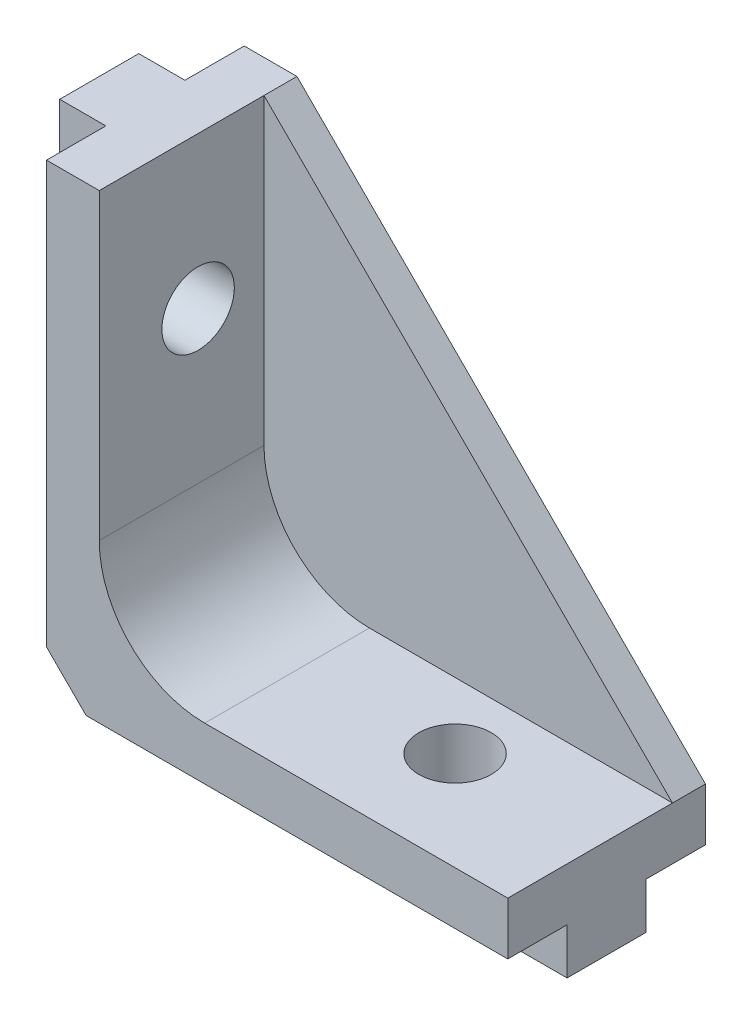
SolidWorks part; units mm, degrees
ref_plane "Front" through (0, 0, 0) normal (0, 0, 1) x (1, 0, 0)
ref_plane "Top" through (0, 0, 0) normal (0, 1, 0) x (1, 0, 0)
ref_plane "Right" through (0, 0, 0) normal (1, 0, 0) x (0, 0, -1)
sketch "Sketch1" plane through (0, 0, 0) normal (0, 0, 1) x (1, 0, 0)
  line L0 (0, 0) -> (0, 35)
  line L1 (0, 35) -> (4, 35)
  line L2 (4, 35) -> (35, 4)
  line L3 (35, 4) -> (35, 0)
  line L4 (35, 0) -> (0, 0)
  dimension "D1" = 4
  dimension "D2" = 35
extrude "Boss-Extrude1" add sketch "Sketch1" along normal blind 2.5
sketch "Sketch2" plane through (0, 0, 2.5) normal (0, 0, 1) x (1, 0, 0)
  line L0 (35, 0) -> (35, 4) construction
  line L1 (0, 0) -> (35, 0) construction
  line L2 (4, 35) -> (0, 35) construction
  line L3 (0, 35) -> (0, 0) construction
  line L4 (35, 0) -> (35, 4)
  line L5 (0, 0) -> (35, 0)
  line L6 (4, 35) -> (0, 35)
  line L7 (0, 35) -> (0, 0)
  line L8 (4, 35) -> (4, 4)
  line L9 (4, 4) -> (35, 4)
extrude "Boss-Extrude2" add sketch "Sketch2" along normal blind 12.5
sketch "Sketch5" plane through (0, 0, 0) normal (0, -1, 0) x (1, 0, 0)
  line L0 (35, 15) -> (35, 0) construction
  line L1 (35, 10.5) -> (4.5, 10.5)
  line L2 (35, 10.5) -> (35, 4.5)
  line L3 (35, 4.5) -> (4.5, 4.5)
  line L4 (4.5, 10.5) -> (4.5, 4.5)
  point P7 (35, 7.5)
  point P8 (35, 7.5)
  dimension "D1" = 30.5
  dimension "D2" = 6
extrude "Boss-Extrude3" add sketch "Sketch5" along normal blind 3.5
sketch "Sketch6" plane through (0, 0, 0) normal (-1, 0, 0) x (0, 0, 1)
  line L0 (15, 35) -> (0, 35) construction
  line L1 (10.5, 35) -> (4.5, 35)
  line L2 (10.5, 35) -> (10.5, 4.5)
  line L3 (10.5, 4.5) -> (4.5, 4.5)
  line L4 (4.5, 35) -> (4.5, 4.5)
  point P6 (7.5, 35)
  point P7 (7.5, 35)
  dimension "D1" = 6
  dimension "D2" = 30.5
extrude "Boss-Extrude4" add sketch "Sketch6" along normal blind 3.5
sketch "Sketch3" plane through (4, 0, 0) normal (1, 0, 0) x (0, 0, -1)
  line L0 (-7.5, 35) -> (-7.5, 23.5) construction
  line L1 (-10.5, 35) -> (-4.5, 35) construction
  line L2 (-7.5, 23.5) -> (-7.5, 0) construction
  line L5 (-15, 0) -> (0, 0) construction
  circle A0 centre (-7.5, 23.5) radius 2.75
  point P7 (-7.5, 35)
  point P10 (-7.5, 0)
  dimension "D1" = 5.5
  dimension "D2" = 23.5
extrude "Cut-Extrude1" cut sketch "Sketch3" against normal up to next
sketch "Sketch4" plane through (0, 4, 0) normal (0, 1, 0) x (1, 0, 0)
  line L0 (0, -7.5) -> (23.5, -7.5) construction
  line L2 (23.5, -7.5) -> (35, -7.5) construction
  line L4 (0, -15) -> (0, 0) construction
  line L6 (35, -4.5) -> (35, -10.5) construction
  circle A0 centre (23.5, -7.5) radius 2.75
  point P7 (0, -7.5)
  point P13 (35, -7.5)
  dimension "D1" = 5.5
  dimension "D2" = 23.5
extrude "Cut-Extrude2" cut sketch "Sketch4" against normal up to next
fillet "Fillet1" radius 8 1 edges at (4, 4, 8.75)
chamfer "Chamfer1" distance 3 angle 45 1 edges at (0, 0, 7.5)
